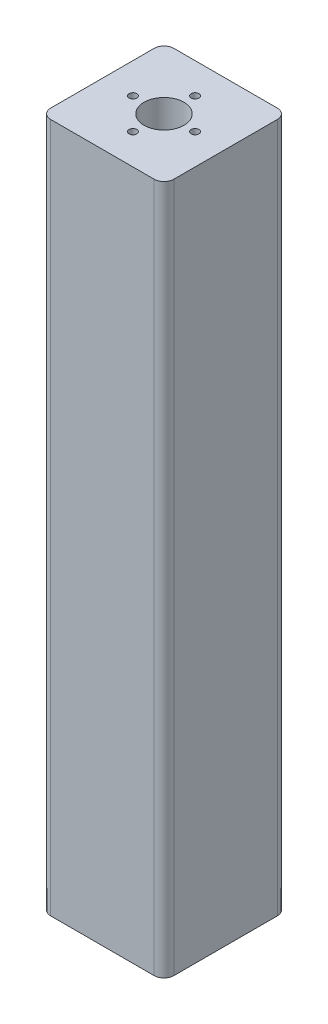
SolidWorks part; units mm, degrees
ref_plane "Front Plane" through (0, 0, 0) normal (0, 0, 1) x (1, 0, 0)
ref_plane "Top Plane" through (0, 0, 0) normal (0, 1, 0) x (1, 0, 0)
ref_plane "Right Plane" through (0, 0, 0) normal (1, 0, 0) x (0, 0, -1)
sketch "Sketch1" plane through (0, 0, 0) normal (0, 1, 0) x (1, 0, 0)
  line L1 (15.875, 15.875) -> (-15.875, 15.875)
  line L2 (15.875, 15.875) -> (15.875, -15.875)
  line L3 (15.875, -15.875) -> (-15.875, -15.875)
  line L4 (-15.875, 15.875) -> (-15.875, -15.875)
  line L5 (15.875, 15.875) -> (-15.875, -15.875) construction
  line L6 (15.875, -15.875) -> (-15.875, 15.875) construction
  point P0 (0, 0)
  dimension "D1" = 31.75
  dimension "D2" = 31.75
extrude "Boss-Extrude1" add sketch "Sketch1" along normal blind 177.8
sketch "Sketch2" plane through (0, 177.8, 0) normal (0, 1, 0) x (1, 0, 0)
  line L0 (0, -8) -> (0, 8) construction
  line L1 (8, 0) -> (-8, 0) construction
  circle A0 centre (0, 0) radius 8 construction
  circle A1 centre (0, 8) radius 1
  circle A2 centre (0, -8) radius 1
  circle A3 centre (-8, 0) radius 1
  circle A4 centre (8, 0) radius 1
  point P11 (-7.9932, -0.3309)
  point P13 (7.9926, -0.3435)
  dimension "D1" = 16
  dimension "D2" = 2
extrude "Cut-Extrude1" cut sketch "Sketch2" against normal blind 38.1
fillet "Fillet1" radius 2.54 4 edges at (15.875, 88.9, -15.875) (-15.875, 88.9, -15.875) (15.875, 88.9, 15.875) (-15.875, 88.9, 15.875)
sketch "Sketch3" plane through (0, 177.8, 0) normal (0, 1, 0) x (1, 0, 0)
  circle A0 centre (0, 0) radius 5.15
  dimension "D1" = 10.3
extrude "Cut-Extrude2" cut sketch "Sketch3" against normal blind 165.1
sketch "Sketch4" plane through (0, 0, 0) normal (0, -1, 0) x (1, 0, 0)
  circle A0 centre (0, 0) radius 1
  dimension "D1" = 2
extrude "Cut-Extrude3" cut sketch "Sketch4" against normal through all
